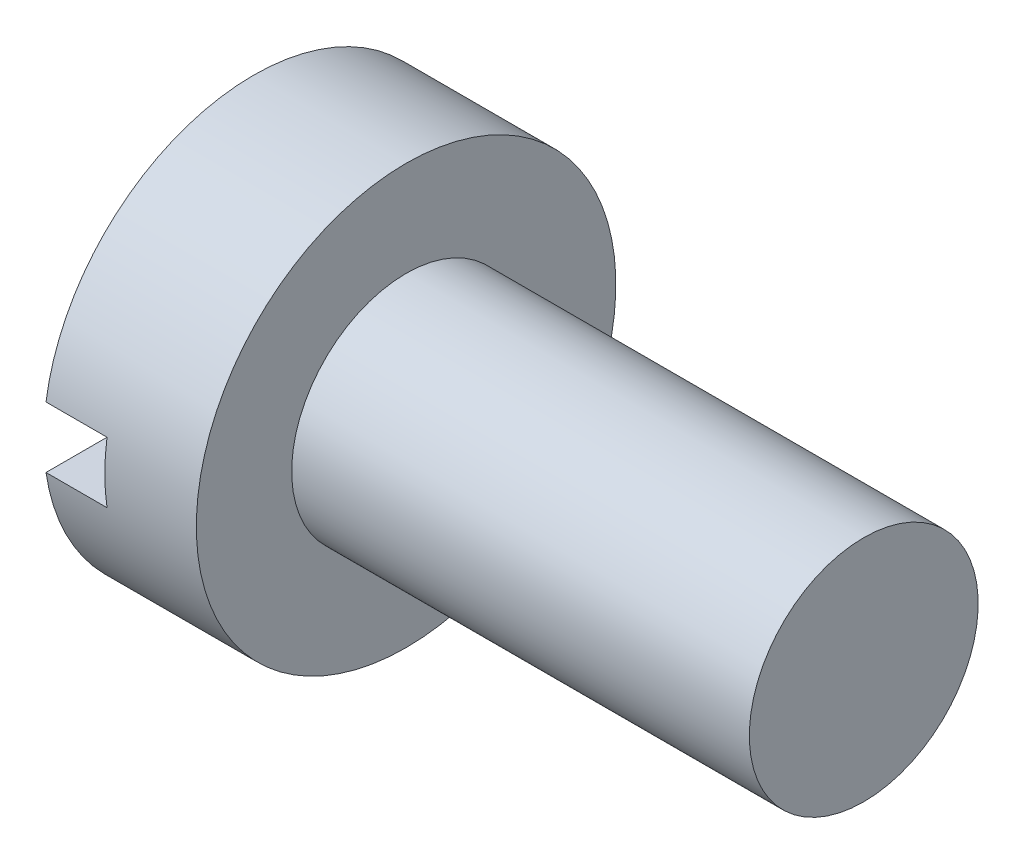
SolidWorks part; units mm, degrees
material "Plain Carbon Steel"
ref_plane "Front Plane" through (0, 0, 0) normal (0, 0, 1) x (1, 0, 0)
ref_plane "Top Plane" through (0, 0, 0) normal (0, 1, 0) x (1, 0, 0)
ref_plane "Right Plane" through (0, 0, 0) normal (1, 0, 0) x (0, 0, -1)
sketch "Sketch1" plane through (0, 0, 0) normal (0, 0, 1) x (1, 0, 0)
  line L0 (0, 0) -> (0, 2.75)
  line L1 (0, 2.75) -> (2, 2.75)
  line L2 (2, 2.75) -> (2, 1.5)
  line L3 (2, 1.5) -> (8, 1.5)
  line L4 (8, 1.5) -> (8, 0)
  line L5 (8, 0) -> (0, 0) construction
  line L6 (0, 0) -> (8, 0)
  dimension "D1" = 3
  dimension "D2" = 6
  dimension "D3" = 5.5
  dimension "D4" = 2
revolve "Revolve1" add sketch "Sketch1" angle 360 about L5
sketch "Sketch2" plane through (0, 0, 0) normal (-1, 0, 0) x (0, 0, 1)
  line L0 (2.75, 0) -> (-2.75, 0) construction
  line L1 (-2.75, 0.4) -> (2.75, 0.4)
  line L2 (-2.75, 0.4) -> (-2.75, -0.4)
  line L3 (-2.75, -0.4) -> (2.75, -0.4)
  line L4 (2.75, 0.4) -> (2.75, -0.4)
  circle A0 centre (0, 0) radius 2.75 construction
  dimension "D1" = 0.8
extrude "Cut-Extrude1" cut sketch "Sketch2" against normal blind 0.8
